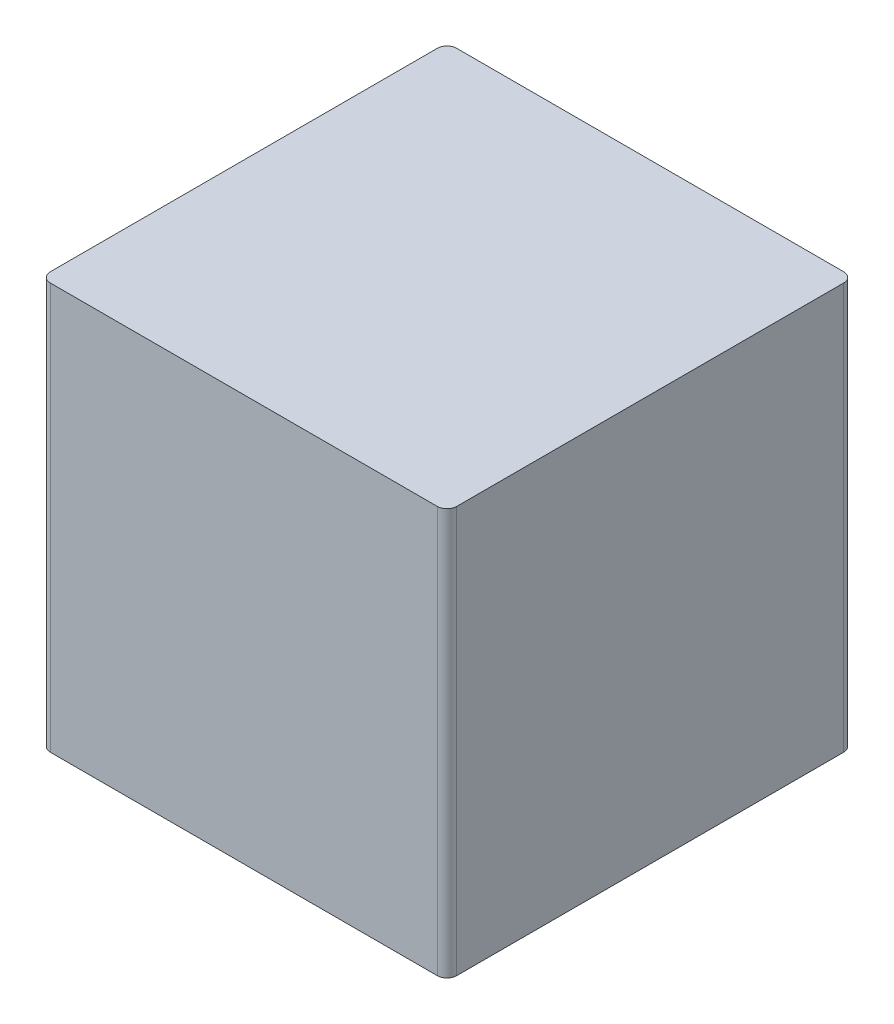
SolidWorks part; units mm, degrees
ref_plane "Ebene vorne" through (0, 0, 0) normal (0, 0, 1) x (1, 0, 0)
ref_plane "Ebene oben" through (0, 0, 0) normal (0, 1, 0) x (1, 0, 0)
ref_plane "Ebene rechts" through (0, 0, 0) normal (1, 0, 0) x (0, 0, -1)
sketch "Skizze1" plane through (0, 0, 0) normal (0, 1, 0) x (1, 0, 0)
  line L5 (0, 0) -> (42, 0)
  line L6 (0, 0) -> (0, 42)
  line L7 (0, 42) -> (42, 42)
  line L8 (42, 0) -> (42, 42)
  line L9 (0, 0) -> (42, 42) construction
  line L10 (0, 42) -> (42, 0) construction
  point P8 (21, 21)
  dimension "D1" = 42
  dimension "D2" = 42
extrude "Aufsatz-Linear austragen1" add sketch "Skizze1" along normal blind 42
fillet "Verrundung1" radius 1 4 edges at (42, 21, -42) (42, 21, 0) (0, 21, 0) (0, 21, -42)
sketch "Skizze2" plane through (0, 0, 0) normal (0, 1, 0) x (1, 0, 0)
  line L0 (0, 41) -> (0, 1) construction
  line L1 (0.75, 41.25) -> (41.25, 41.25)
  line L2 (0.75, 41.25) -> (0.75, 0.75)
  line L3 (0.75, 0.75) -> (41.25, 0.75)
  line L4 (41.25, 41.25) -> (41.25, 0.75)
  line L5 (0.75, 41.25) -> (41.25, 0.75) construction
  line L6 (0.75, 0.75) -> (41.25, 41.25) construction
  line L7 (1, 0) -> (41, 0) construction
  point P0 (21, 21)
  point P7 (21, 21)
  dimension "D1" = 40.5
  dimension "D2" = 40.5
  dimension "D3" = 0.75
  dimension "D4" = 0.75
extrude "Schnitt-Linear austragen1" cut sketch "Skizze2" along normal blind 1
